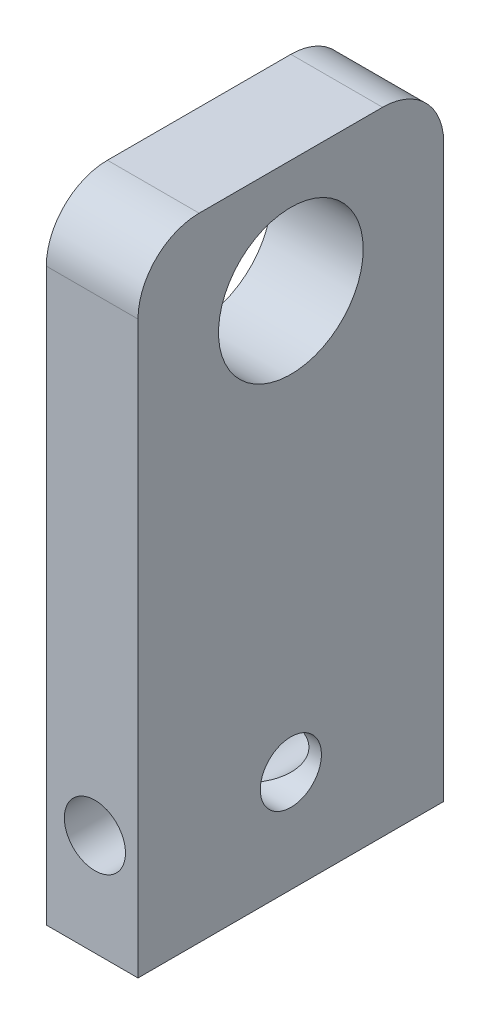
SolidWorks part; units mm, degrees
ref_plane "Front Plane" through (0, 0, 0) normal (0, 0, 1) x (1, 0, 0)
ref_plane "Top Plane" through (0, 0, 0) normal (0, 1, 0) x (1, 0, 0)
ref_plane "Right Plane" through (0, 0, 0) normal (1, 0, 0) x (0, 0, -1)
sketch "Sketch1" plane through (0, 0, 0) normal (0, 1, 0) x (1, 0, 0)
  line L1 (-2.3864, 13.6636) -> (2.1136, 13.6636)
  line L2 (-2.3864, 13.6636) -> (-2.3864, -1.3364)
  line L3 (-2.3864, -1.3364) -> (2.1136, -1.3364)
  line L4 (2.1136, 13.6636) -> (2.1136, -1.3364)
  dimension "D1" = 4.5
  dimension "D2" = 15
extrude "Boss-Extrude1" add sketch "Sketch1" along normal blind 31
sketch "Sketch2" plane through (2.1136, 0, 0) normal (1, 0, 0) x (0, 0, -1)
  line L0 (-1.3364, 31) -> (13.6636, 31) construction
  circle A0 centre (6.1636, 25.45) radius 3.55
  point P2 (6.1636, 31)
  dimension "D1" = 5.55
  dimension "D2" = 7.1
extrude "Cut-Extrude1" cut sketch "Sketch2" against normal blind 20
sketch "Sketch3" plane through (-2.3864, 0, 0) normal (-1, 0, 0) x (0, 0, 1)
  line L0 (-13.6636, 0) -> (1.3364, 0) construction
  circle A0 centre (-6.1636, 5) radius 1.5
  dimension "D1" = 3
  dimension "D2" = 5
extrude "Cut-Extrude2" cut sketch "Sketch3" against normal blind 20
sketch "Sketch4" plane through (0, 0, -13.6636) normal (0, 0, -1) x (-1, 0, 0)
  line L0 (-2.1136, 0) -> (2.3864, 0) construction
  circle A0 centre (0, 5) radius 1.5
  dimension "D1" = 3
  dimension "D2" = 5
extrude "Cut-Extrude3" cut sketch "Sketch4" against normal blind 20
fillet "Fillet1" radius 3 1 edges at (-0.1364, 31, 1.3364)
fillet "Fillet2" radius 3 1 edges at (-0.1364, 31, -13.6636)
